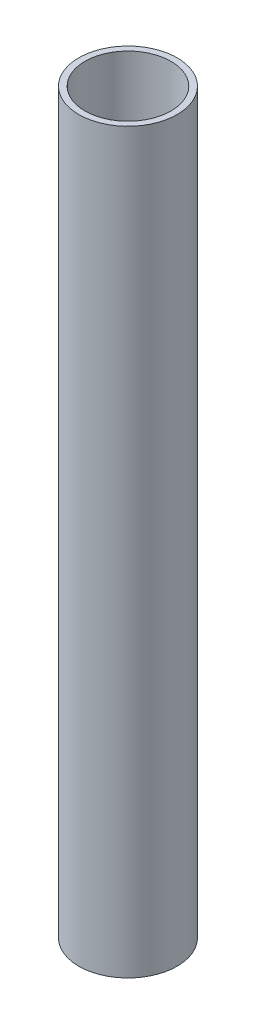
SolidWorks part; units mm, degrees
ref_plane "Front Plane" through (0, 0, 0) normal (0, 0, 1) x (1, 0, 0)
ref_plane "Top Plane" through (0, 0, 0) normal (0, 1, 0) x (1, 0, 0)
ref_plane "Right Plane" through (0, 0, 0) normal (1, 0, 0) x (0, 0, -1)
sketch "Sketch1" plane through (0, 0, 0) normal (0, 1, 0) x (1, 0, 0)
  circle A0 centre (0, 0) radius 8
  circle A1 centre (0, 0) radius 7
extrude "Boss-Extrude1" add sketch "Sketch1" along normal blind 120
